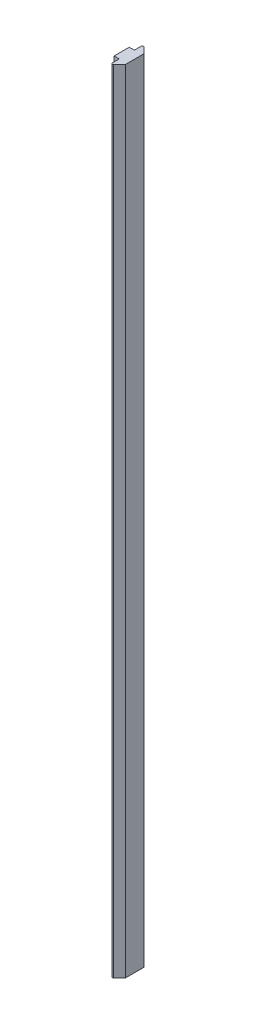
SolidWorks part; units mm, degrees
ref_plane "Front Plane" through (0, 0, 0) normal (0, 0, 1) x (1, 0, 0)
ref_plane "Top Plane" through (0, 0, 0) normal (0, 1, 0) x (1, 0, 0)
ref_plane "Right Plane" through (0, 0, 0) normal (1, 0, 0) x (0, 0, -1)
sketch "Sketch1" plane through (0, 0, 0) normal (0, 1, 0) x (1, 0, 0)
  line L0 (-4.6893, 3.1281) -> (-4.6893, 3.6281) construction
  line L1 (-4.6893, 3.6281) -> (-5.1893, 3.6281) construction
  line L2 (-4.7927, -3.1458) -> (-4.7927, -3.1281) construction
  line L3 (-5.1893, -3.1458) -> (-4.7927, -3.1458) construction
  line L6 (-4.7927, -3.1281) -> (-3.4893, -3.1281) construction
  line L7 (-3.4893, 3.1281) -> (-4.6893, 3.1281) construction
  line L8 (-2.2944, -5.9224) -> (0, -3.6281) construction
  line L9 (-3.4893, -3.1281) -> (-3.4893, -5.4274) construction
  line L10 (-3.4893, 5.4274) -> (-3.4893, 3.1281) construction
  line L11 (0, 3.6281) -> (-2.2944, 5.9224) construction
  line L12 (0, 3.6281) -> (0, -3.6281) construction
  line L14 (-3.2393, -2.8781) -> (-3.2393, -5.4274)
  line L15 (-2.4711, -5.7456) -> (-0.25, -3.5245)
  line L16 (-0.25, 3.5245) -> (-0.25, -3.5245)
  line L17 (-0.25, 3.5245) -> (-2.4711, 5.7456)
  line L18 (-3.2393, 5.4274) -> (-3.2393, 2.8781)
  line L19 (-3.2393, 2.8781) -> (-4.9393, 2.8781)
  line L22 (-5.1893, 2.8781) -> (-5.1893, -2.8781)
  line L23 (-3.2393, -2.8781) -> (-5.1893, -2.8781)
  line L24 (-5.1893, -2.8958) -> (-5.0427, -2.8958) construction
  line L25 (-5.0427, -2.8958) -> (-5.0427, -2.8781) construction
  line L26 (-5.0427, -2.8781) -> (-3.2393, -2.8781) construction
  line L27 (-4.9393, 2.8781) -> (-4.9393, 3.3781) construction
  line L28 (-4.9393, 2.8781) -> (-5.1893, 2.8781)
  line L31 (-4.9393, 3.3781) -> (-5.1893, 3.3781) construction
  arc A0 (-3.2393, -5.4274) -> (-2.4711, -5.7456) centre (-2.7893, -5.4274) ccw
  arc A1 (-2.4711, 5.7456) -> (-3.2393, 5.4274) centre (-2.7893, 5.4274) ccw
  arc A4 (-3.4893, -5.4274) -> (-2.2944, -5.9224) centre (-2.7893, -5.4274) ccw construction
  arc A5 (-2.2944, 5.9224) -> (-3.4893, 5.4274) centre (-2.7893, 5.4274) ccw construction
  point P8 (0, 0)
  dimension "D1" = 0.25
extrude "Boss-Extrude1" add sketch "Sketch1" along normal blind 300
